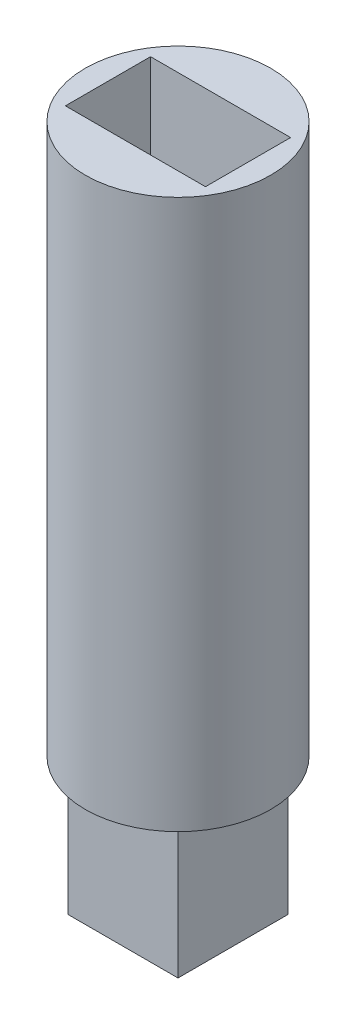
SolidWorks part; units mm, degrees
material "Silicon Rubber"
ref_plane "Front Plane" through (0, 0, 0) normal (0, 0, 1) x (1, 0, 0)
ref_plane "Top Plane" through (0, 0, 0) normal (0, 1, 0) x (1, 0, 0)
ref_plane "Right Plane" through (0, 0, 0) normal (1, 0, 0) x (0, 0, -1)
sketch "Sketch1" plane through (0, 0, 0) normal (0, 1, 0) x (1, 0, 0)
  circle A0 centre (0, 0) radius 3.375
  dimension "D1" = 6.75
extrude "Boss-Extrude1" add sketch "Sketch1" along normal blind 20
sketch "Sketch2" plane through (0, 0, 0) normal (0, -1, 0) x (-1, 0, 0)
  line L1 (2, -2) -> (-2, -2)
  line L2 (2, -2) -> (2, 2)
  line L3 (2, 2) -> (-2, 2)
  line L4 (-2, -2) -> (-2, 2)
  line L5 (2, -2) -> (-2, 2) construction
  line L6 (2, 2) -> (-2, -2) construction
  point P0 (0, 0)
  dimension "D1" = 4
  dimension "D2" = 4
sketch "Sketch3" plane through (0, 20, 0) normal (0, 1, 0) x (1, 0, 0)
  line L1 (-2.55, 1.55) -> (2.55, 1.55)
  line L2 (-2.55, 1.55) -> (-2.55, -1.55)
  line L3 (-2.55, -1.55) -> (2.55, -1.55)
  line L4 (2.55, 1.55) -> (2.55, -1.55)
  line L5 (-2.55, 1.55) -> (2.55, -1.55) construction
  line L6 (-2.55, -1.55) -> (2.55, 1.55) construction
  point P0 (0, 0)
  dimension "D1" = 3.1
  dimension "D2" = 5.1
extrude "Cut-Extrude2" cut sketch "Sketch3" against normal blind 6
extrude "Boss-Extrude2" add sketch "Sketch2" along normal blind 5
